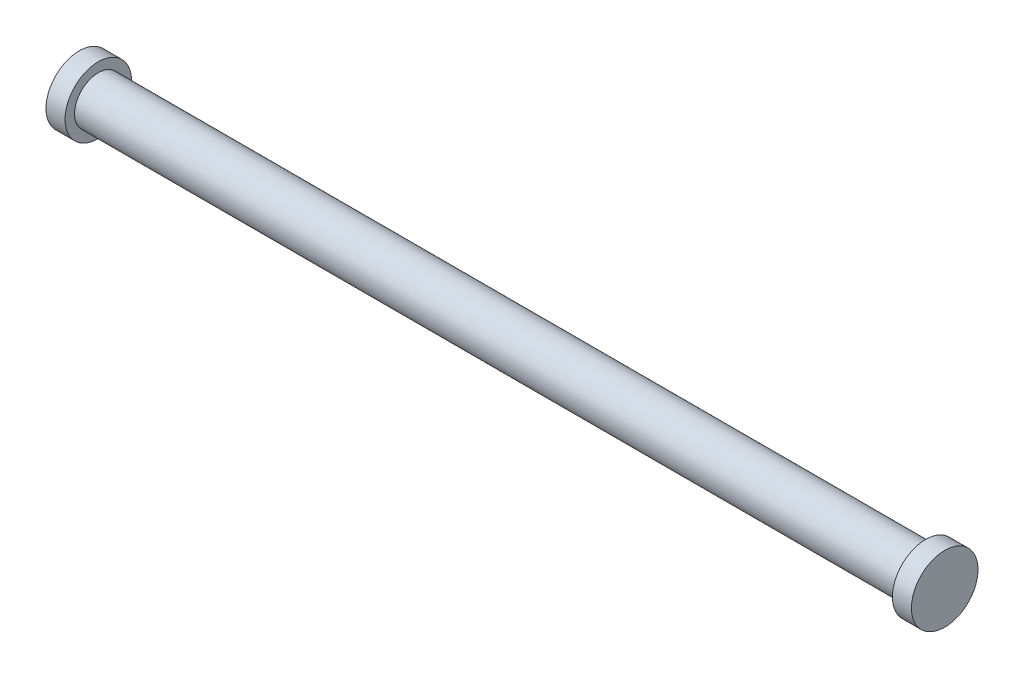
SolidWorks part; units mm, degrees
ref_plane "Front Plane" through (0, 0, 0) normal (0, 0, 1) x (1, 0, 0)
ref_plane "Top Plane" through (0, 0, 0) normal (0, 1, 0) x (1, 0, 0)
ref_plane "Right Plane" through (0, 0, 0) normal (1, 0, 0) x (0, 0, -1)
sketch "Sketch1" plane through (0, 0, 0) normal (1, 0, 0) x (0, 0, -1)
  circle A0 centre (0, 0) radius 12.5
  dimension "D1" = 25
extrude "Boss-Extrude1" add sketch "Sketch1" against normal blind 434.9
sketch "Sketch3" plane through (0, 0, 0) normal (1, 0, 0) x (0, 0, -1)
  circle A0 centre (0, 0) radius 17.5
  dimension "D1" = 35
extrude "Boss-Extrude3" add sketch "Sketch3" along normal blind 10
sketch "Sketch4" plane through (-434.9, 0, 0) normal (-1, 0, 0) x (0, 0, 1)
  circle A0 centre (0, 0) radius 17.5
  circle A1 centre (0, 0) radius 12.5 construction
  circle A2 centre (0, 0) radius 17.5 construction
extrude "Boss-Extrude4" add sketch "Sketch4" along normal blind 10
